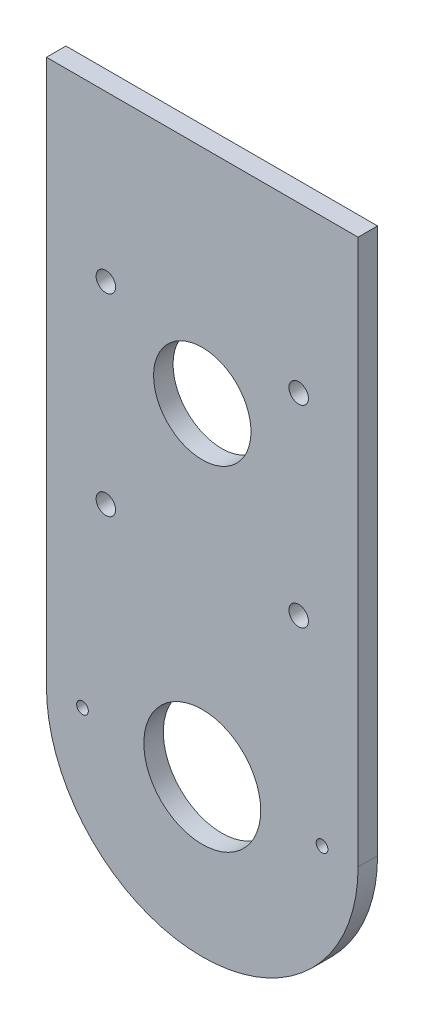
SolidWorks part; units mm, degrees
material "6063-T1"
ref_plane "Front Plane" through (0, 0, 0) normal (0, 0, 1) x (1, 0, 0)
ref_plane "Top Plane" through (0, 0, 0) normal (0, 1, 0) x (1, 0, 0)
ref_plane "Right Plane" through (0, 0, 0) normal (1, 0, 0) x (0, 0, -1)
sketch "Sketch1" plane through (0, 0, 0) normal (0, 0, 1) x (1, 0, 0)
  line L0 (-40, 0) -> (-40, 140)
  line L1 (-40, 140) -> (40, 140)
  line L2 (40, 140) -> (40, 0)
  arc A0 (-40, 0) -> (40, 0) centre (0, 0) ccw
  circle A1 centre (0, 0) radius 15
  dimension "D1" = 80
  dimension "D3" = 30
  dimension "D2" = 140
extrude "Boss-Extrude1" add sketch "Sketch1" along normal blind 5
sketch "Sketch2" plane through (0, 0, 0) normal (0, 0, -1) x (-1, 0, 0)
  line L6 (-30, 43) -> (30, 43) construction
  line L7 (-30, 43) -> (-30, 103) construction
  line L8 (-30, 103) -> (30, 103) construction
  line L9 (30, 43) -> (30, 103) construction
  line L10 (-30, 43) -> (30, 103) construction
  line L11 (-30, 103) -> (30, 43) construction
  circle A1 centre (-24.75, 97.75) radius 2.5
  circle A2 centre (24.75, 97.75) radius 2.5
  circle A3 centre (24.75, 48.25) radius 2.5
  circle A4 centre (-24.75, 48.25) radius 2.5
  circle A5 centre (0, 83) radius 12.5
  point P10 (0, 73)
  point P19 (0, 43)
  dimension "D1" = 25
  dimension "D7" = 5
  dimension "D9" = 83
  dimension "D2" = 30
  dimension "D3" = 20
  dimension "D4" = 49.5
  dimension "D5" = 49.5
  dimension "D6" = 60
  dimension "D8" = 60
  dimension "D10" = 5.25
  dimension "D11" = 5.25
extrude "Cut-Extrude1" cut sketch "Sketch2" against normal through all contours A5 | A1 | A2 | A3 | A4
sketch "Sketch3" plane through (0, 0, 0) normal (0, 0, -1) x (-1, 0, 0)
  circle A0 centre (-30.75, 0) radius 1.5
  circle A1 centre (30.75, 0) radius 1.5
  dimension "D1" = 3
  dimension "D2" = 3
  dimension "D3" = 30.75
  dimension "D4" = 30.75
extrude "Cut-Extrude2" cut sketch "Sketch3" against normal blind 10
